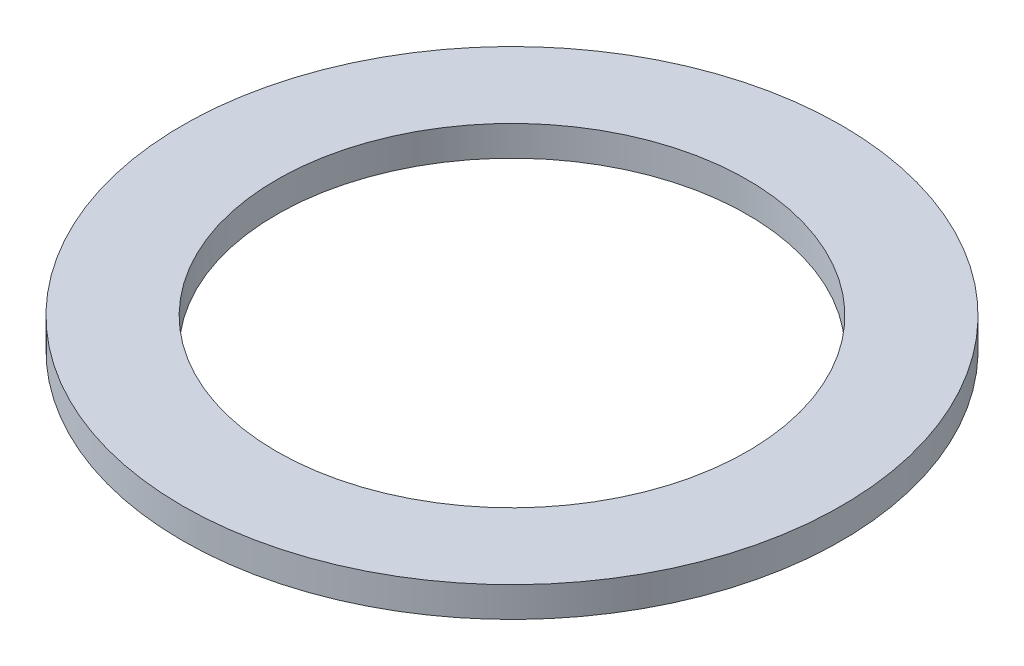
SolidWorks part; units mm, degrees
ref_plane "Front Plane" through (0, 0, 0) normal (0, 0, 1) x (1, 0, 0)
ref_plane "Top Plane" through (0, 0, 0) normal (0, 1, 0) x (1, 0, 0)
ref_plane "Right Plane" through (0, 0, 0) normal (1, 0, 0) x (0, 0, -1)
sketch "Sketch1" plane through (0, 0, 0) normal (0, 1, 0) x (1, 0, 0)
  circle A0 centre (0, 0) radius 5.5562
  dimension "OD" = 11.1125
extrude "Boss-Extrude1" add sketch "Sketch1" along normal blind 0.508
sketch "Sketch5" plane through (0, 0.508, 0) normal (0, 1, 0) x (-1, 0, 0)
  circle A0 centre (0, 0) radius 3.9688
  dimension "ID" = 7.9375
extrude "Cut-Extrude1" cut sketch "Sketch5" against normal through all
